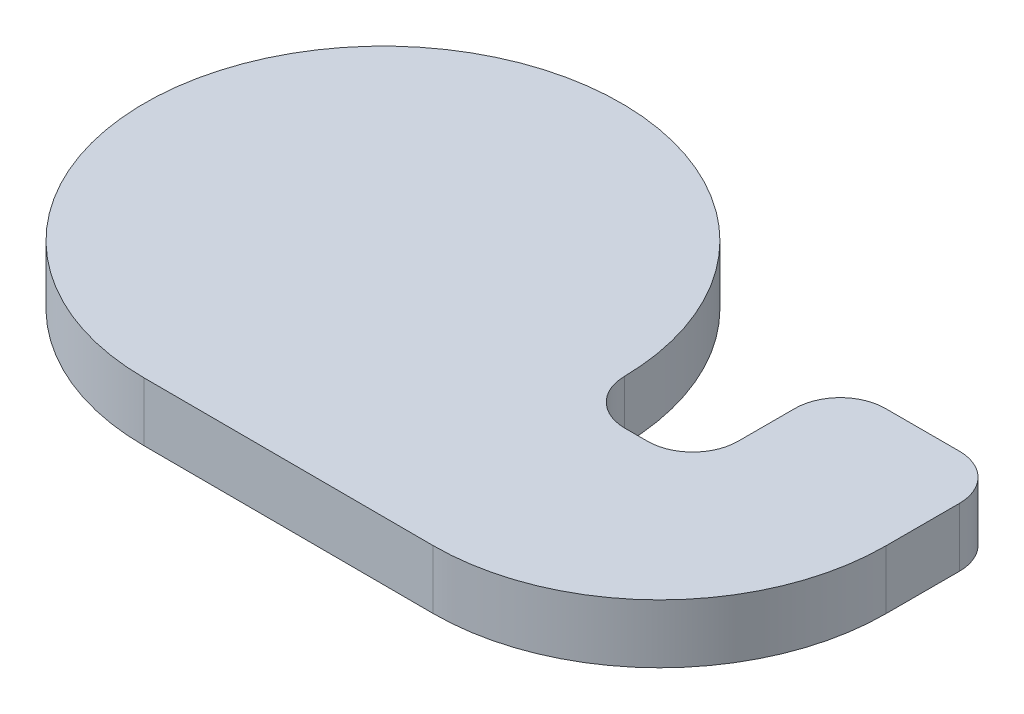
SolidWorks part; units mm, degrees
ref_plane "Płaszczyzna przednia" through (0, 0, 0) normal (0, 0, 1) x (1, 0, 0)
ref_plane "Płaszczyzna górna" through (0, 0, 0) normal (0, 1, 0) x (1, 0, 0)
ref_plane "Płaszczyzna prawa" through (0, 0, 0) normal (1, 0, 0) x (0, 0, -1)
sketch "Sketch1" plane through (0, 0, 0) normal (0, 1, 0) x (1, 0, 0)
  line L1 (11.8641, 0) -> (13.8641, 0)
  line L3 (35.8641, 0) -> (37.8641, 0)
  line L4 (13.8641, 0) -> (15.8641, 0)
  line L5 (33.8641, 0) -> (35.8641, 0)
  line L6 (34.8037, 18.5) -> (51.8037, 18.5)
  line L7 (36.8037, 16.5) -> (49.8037, 16.5)
  line L8 (36.8037, 16.5) -> (36.8037, -8.5)
  line L9 (36.8037, -8.5) -> (49.8037, -8.5)
  line L10 (49.8037, 16.5) -> (49.8037, -8.5)
  line L11 (51.8037, 18.5) -> (51.8037, -10.5)
  line L12 (34.8037, -10.5) -> (51.8037, -10.5)
  line L13 (34.8037, 18.5) -> (34.8037, -10.5)
  line L14 (15.7604, 9.2803) -> (14.1767, 2.6036)
  circle A0 centre (24.8641, 0) radius 7
  circle A1 centre (24.8641, 0) radius 9
  circle A3 centre (24.8641, 0) radius 11
  arc A4 (37.8641, 0) -> (15.7604, 9.2803) centre (24.8641, 0) ccw
  circle A5 centre (24.8641, 0) radius 13 construction
  dimension "D1" = 2
  dimension "D2" = 18
  dimension "D8" = 14
  dimension "D5" = 13
  dimension "D6" = 25
  dimension "D7" = 16.5
  dimension "D3" = 2
  dimension "D4" = 2
sketch "Sketch3" plane through (0, 0, 0) normal (0, 1, 0) x (1, 0, 0)
  line L0 (24.8373, -10.5332) -> (37.638, -10.5658)
  line L3 (37.3962, -1.8334) -> (38.3933, -1.8334)
  line L4 (40.3933, 0.1666) -> (40.3933, 2.6809)
  line L5 (42.3933, 4.6809) -> (45.6634, 4.6809)
  line L6 (47.6634, 2.6809) -> (47.6634, -0.5658)
  line L7 (47.6634, -10.5865) -> (45.7727, -10.5865)
  arc A0 (35.3964, 0.14) -> (24.8373, -10.5332) centre (24.8641, 0) ccw
  arc A3 (37.3962, -1.8334) -> (35.3964, 0.14) centre (37.3962, 0.1666) cw
  circle A6 centre (43.9846, 0) radius 2.2221
  arc A7 (37.638, -10.5658) -> (47.6634, -0.5658) centre (37.6634, -0.5658) ccw
  arc A8 (38.3933, -1.8334) -> (40.3933, 0.1666) centre (38.3933, 0.1666) ccw
  arc A9 (45.6634, 4.6809) -> (47.6634, 2.6809) centre (45.6634, 2.6809) cw
  arc A10 (40.3933, 2.6809) -> (42.3933, 4.6809) centre (42.3933, 2.6809) cw
  dimension "D1" = 10
  dimension "D2" = 2
  dimension "D3" = 2
  dimension "D4" = 2
extrude "Boss-Extrude1" add sketch "Sketch3" against normal blind 2.6 from offset 0.2 contours A3 A0 L0 A7 L6 A9 L5 A10 L4 A8 L3 offset against normal yes
